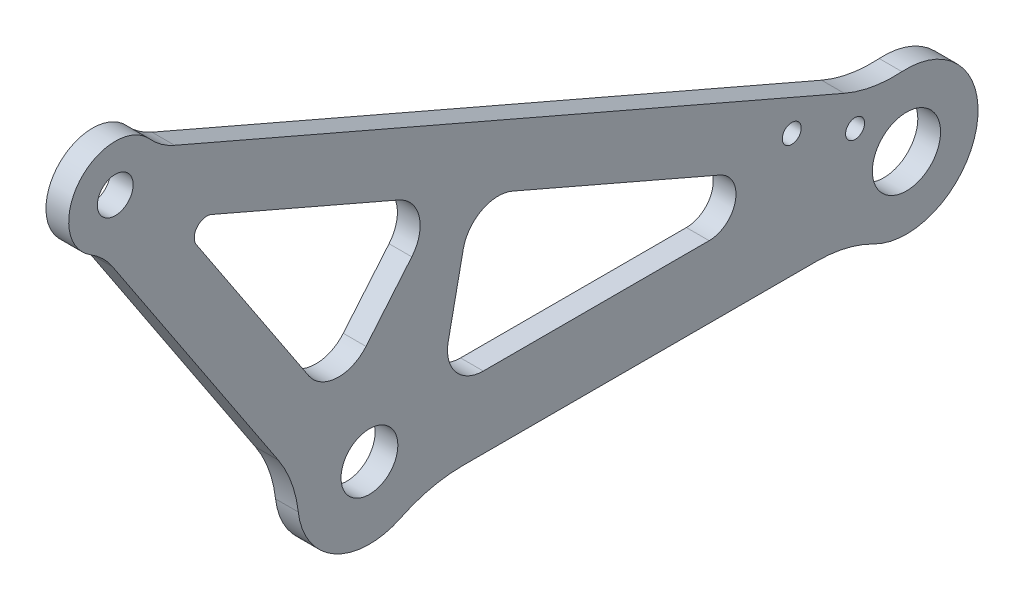
SolidWorks part; units mm, degrees
material "AISI 1020"
ref_plane "Front Plane" through (0, 0, 0) normal (0, 0, 1) x (1, 0, 0)
ref_plane "Top Plane" through (0, 0, 0) normal (0, 1, 0) x (1, 0, 0)
ref_plane "Right Plane" through (0, 0, 0) normal (1, 0, 0) x (0, 0, -1)
sketch "Sketch1" plane through (0, 0, 0) normal (1, 0, 0) x (0, 0, -1)
  line L0 (-60.7171, 0) -> (60.7171, 0)
  line L3 (0, -143.7223) -> (0, 143.7223) construction
  line L4 (-149.7529, 101.5535) -> (-94.5581, 18.1812)
  line L5 (-134.4049, 119.8783) -> (67.4524, 32.5212)
  line L6 (-75, 14) -> (75, 14) construction
  line L8 (-146, 114) -> (-75, 14) construction
  arc A20 (-134.4049, 119.8783) -> (-149.7529, 101.5535) centre (-146, 114) ccw
  arc A22 (-94.5581, 18.1812) -> (-60.7171, 0) centre (-75, 14) ccw
  arc A23 (60.7171, 0) -> (67.4524, 32.5212) centre (75, 14) ccw
  point P5 (0, 0)
  point P14 (0, 0)
  dimension "D3" = 20
  dimension "D5" = 13
  dimension "D6" = 20
  dimension "D4" = 127
  dimension "D7" = 254
  dimension "D10" = 6
  dimension "D11" = 6
  dimension "D9" = 3
  dimension "D12" = 3
  dimension "D13" = 6
  dimension "D14" = 6
  dimension "D2" = 150
  dimension "D8" = 122.6418
extrude "Boss-Extrude1" add sketch "Sketch1" along normal blind 6.35
hole_wizard "3/4 (0.75) Diameter Hole1" positions "Sketch4" profile "Sketch3" hole size "3/4" standard "ANSI Inch" end condition up to next
sketch "Sketch4" plane through (6.35, 0, 0) normal (1, 0, 0) x (0, 0, -1)
  point P5 (75, 14)
sketch "Sketch3" plane through (6.35, 14, -75) normal (0, 1, 0) x (0, 0, -1)
  line L0 (0, 0) -> (0, 6.35)
  line L1 (0, 6.35) -> (9.525, 6.35)
  line L2 (9.525, 6.35) -> (9.525, 0)
  line L5 (9.525, 0) -> (0, 0)
  line L11 (0, -6.35) -> (0, 107.95) construction
  dimension "Thru Hole Dia." = 19.05
  dimension "Thru Hole Depth" = 6.35
hole_wizard "Ø10.0 (10) Diameter Hole1" positions "Sketch9" profile "Sketch6" hole size "Ø10.0" standard "ANSI Metric" end condition up to next
sketch "Sketch9" plane through (6.35, 0, 0) normal (1, 0, 0) x (0, 0, -1)
  point P0 (-146, 114)
sketch "Sketch6" plane through (6.35, 114, 146) normal (0, 1, 0) x (0, 0, -1)
  line L0 (0, 0) -> (0, 6.35)
  line L1 (0, 6.35) -> (5, 6.35)
  line L2 (5, 6.35) -> (5, 0)
  line L5 (5, 0) -> (0, 0)
  line L11 (0, -6.35) -> (0, 107.95) construction
  dimension "Thru Hole Dia." = 10
  dimension "Thru Hole Depth" = 6.35
hole_wizard "Ø5/8\" Diameter Hole2" positions "Sketch16" profile "Sketch11" hole size "5/8" standard "ANSI Inch" end condition up to next
sketch "Sketch16" plane through (6.35, 0, 0) normal (1, 0, 0) x (0, 0, -1)
  line L0 (75, 14) -> (157.5513, 156.983)
  line L2 (0, 0) -> (0, 108.153) construction
  line L4 (-146, 114) -> (-119.4521, 194.8786)
  line L6 (-174.545, 70.324) -> (-178.0536, 59.6351) construction
  line L7 (-174.545, 70.324) -> (-178.0536, 59.6351) construction
  arc A0 (-94.5581, 18.1812) -> (-60.7171, 0) centre (-75, 14) ccw construction
  point P0 (-75, 14)
  dimension "D1" = 30
sketch "Sketch11" plane through (6.35, 14, 75) normal (0, 1, 0) x (0, 0, -1)
  line L0 (0, 0) -> (0, 6.35)
  line L1 (0, 6.35) -> (7.9375, 6.35)
  line L2 (7.9375, 6.35) -> (7.9375, 0)
  line L5 (7.9375, 0) -> (0, 0)
  line L11 (0, -6.35) -> (0, 107.95) construction
  dimension "Thru Hole Dia." = 15.875
  dimension "Thru Hole Depth" = 6.35
sketch "Sketch8" plane through (6.35, 0, 0) normal (1, 0, 0) x (0, 0, -1)
  line L2 (-54.5605, 67.8903) -> (-46.3008, 64.3157) construction
  line L3 (-52.9877, 32.028) -> (-48.7918, 52.2877)
  line L7 (-75.9573, 42.3434) -> (-63.1664, 57.6152)
  line L9 (-123.3455, 90.6494) -> (-91.9619, 43.2441)
  line L10 (-119.037, 95.7935) -> (-66.861, 73.2135)
  line L11 (19.8861, 20) -> (-43.1955, 20)
  line L12 (67.4524, 32.5212) -> (-134.4049, 119.8783) construction
  line L13 (-149.7529, 101.5535) -> (-94.5581, 18.1812) construction
  line L14 (-60.7171, 0) -> (60.7171, 0) construction
  line L15 (-84.5632, 32.0683) -> (-84.2827, 31.6447) construction
  line L16 (-55.4787, 20) -> (-55.9867, 20) construction
  line L17 (-54.5605, 67.8903) -> (-46.3008, 64.3157) construction
  line L18 (-35.0279, 59.4372) -> (22.8649, 34.3831)
  line L19 (-120.4271, 92.5814) -> (-104.3957, 79.1543) construction
  line L20 (19.8861, 27.5) -> (27.9693, 25.826) construction
  line L21 (-29.8567, 10) -> (10.3311, 10) construction
  arc A0 (-52.9877, 32.028) -> (-43.1955, 20) centre (-43.1955, 30) ccw
  arc A2 (-48.7918, 52.2877) -> (-35.0279, 59.4372) centre (-38.9996, 50.2597) cw
  arc A4 (-63.1664, 57.6152) -> (-66.861, 73.2135) centre (-70.8327, 64.0361) ccw
  arc A14 (-119.037, 95.7935) -> (-123.3455, 90.6494) centre (-120.4271, 92.5814) ccw
  arc A20 (-75.9573, 42.3434) -> (-91.9619, 43.2441) centre (-83.6236, 48.7643) cw
  arc A25 (-134.4049, 119.8783) -> (-149.7529, 101.5535) centre (-146, 114) ccw construction
  circle A27 centre (-146, 114) radius 5 construction
  arc A36 (-94.5581, 18.1812) -> (-60.7171, 0) centre (-75, 14) ccw construction
  circle A39 centre (-75, 14) radius 7.9375 construction
  arc A40 (19.8861, 20) -> (22.8649, 34.3831) centre (19.8861, 27.5) ccw
  circle A54 centre (-75, 14) radius 19.9375
  arc A55 (-55.9867, 20) -> (-84.2827, 31.6447) centre (-75, 14) ccw construction
  point P7 (-33.5049, 66.1162)
  point P19 (-33.4763, 76.1997)
  dimension "D8" = 8
  dimension "D9" = 12.0625
  dimension "D11" = 9
  dimension "D7" = 4
  dimension "D1" = 7
  dimension "D10" = 24.8576
  dimension "D2" = 15
  dimension "D12" = 10
  dimension "D13" = 14.6862
  dimension "D3" = 12
  dimension "D5" = 16
  dimension "D6" = 20
  dimension "D4" = 16
extrude "Cut-Extrude1" cut sketch "Sketch8" against normal up to next
fillet "Fillet1" radius 35 1 edges at (3.175, 18.1812, 94.5581)
fillet "Fillet3" radius 35 2 edges at (3.175, 32.5212, -67.4524) (3.175, 0, -60.7171)
fillet "Fillet4" radius 20 2 edges at (3.175, 101.5535, 149.7529) (3.175, 119.8783, 134.4049)
fillet "Fillet6" radius 40 1 edges at (3.175, 0, 60.7171)
sketch "Sketch17" [suppressed] plane through (0, 0, 0) normal (-1, 0, 0) x (0, 0, 1)
  line L0 (-31.692, 47.9971) -> (-74.6306, 61.6169)
  line L1 (-57.6351, 36.7697) -> (129.4114, 117.7173) construction
  line L2 (-134.8033, 70.2122) -> (-137.856, 60.5882)
  line L3 (-135.7084, 50.8215) -> (-89.7688, 0.5136)
  line L4 (-57.6351, 36.7697) -> (-31.692, 47.9971)
  line L6 (-84.0792, 16.8799) -> (-65.9208, 11.1201) construction
  line L7 (-100.5678, 75.614) -> (-71.9719, 66.5436) construction
  line L8 (-77.8799, 4.9208) -> (-72.1201, 23.0792) construction
  line L9 (-74.6306, 61.6169) -> (-101.2349, 70.0556) construction
  line L10 (-101.2349, 70.0556) -> (-122.2479, 76.7207)
  arc A0 (-73.7404, 33.9603) -> (-65.9164, -3.8182) centre (-75, 14) ccw construction
  arc A1 (-73.7404, 33.9603) -> (-57.6351, 36.7697) centre (-71.5361, 68.8908) ccw construction
  arc A2 (-73.7404, 33.9603) -> (-89.7688, 0.5136) centre (-75, 14) ccw
  arc A3 (-73.7404, 33.9603) -> (-57.6351, 36.7697) centre (-71.5361, 68.8908) ccw
  arc A4 (-137.856, 60.5882) -> (-135.7084, 50.8215) centre (-128.324, 57.5647) ccw
  arc A5 (-122.2479, 76.7207) -> (-134.8033, 70.2122) centre (-125.2713, 67.1887) ccw
  arc A6 (-101.2349, 70.0556) -> (-74.6306, 61.6169) centre (-86.2698, 71.0788) ccw
  circle A7 centre (-75, 14) radius 9.525 construction
  arc A8 (-71.9719, 66.5436) -> (-100.5678, 75.614) centre (-86.2698, 71.0788) ccw construction
  arc A9 (-100.5678, 75.614) -> (-101.2349, 70.0556) centre (-86.2698, 71.0788) ccw construction
  arc A10 (-74.6306, 61.6169) -> (-71.9719, 66.5436) centre (-86.2698, 71.0788) ccw construction
  point P15 (-75, 14)
  point P18 (-86.2698, 71.0788)
  point P26 (-139.6016, 55.0849)
  point P29 (-131.7798, 79.7442)
  point P31 (-75, 14)
  dimension "D5" = 10
  dimension "D1" = 41
  dimension "D2" = 45.5
  dimension "D3" = 120
  dimension "D4" = 74
  dimension "D6" = 30
  dimension "D7" = 51
  dimension "D8" = 28
extrude "Boss-Extrude2" [suppressed] add sketch "Sketch17" against normal up to surface (6.35 mm away)
hole_wizard "M5 Clearance Hole1" positions "Sketch21" profile "Sketch19" hole size "M5" standard "ANSI Metric"
sketch "Sketch21" [suppressed] plane through (0, 0, 0) normal (-1, 0, 0) x (0, 0, 1)
  line L0 (-125.2509, 66.6577) -> (-73.9498, 50.3854) construction
  line L2 (-31.692, 47.9971) -> (-74.6306, 61.6169) construction
  line L3 (-75, 14) -> (-64.4178, 47.3619) construction
  line L5 (-134.8033, 70.2122) -> (-137.856, 60.5882) construction
  point P1 (-125.2509, 66.6577)
  point P3 (-73.9498, 50.3854)
  dimension "D1" = 35
  dimension "D2" = 10
  dimension "D3" = 53.82
sketch "Sketch19" plane through (0, 66.6577, -125.2509) normal (0, 1, 0) x (0, 0, 1)
  line L0 (0, 0) -> (0, 6.35)
  line L1 (0, 6.35) -> (2.65, 6.35)
  line L2 (2.65, 6.35) -> (2.65, 0)
  line L5 (2.65, 0) -> (0, 0)
  line L11 (0, -6.35) -> (0, 107.95) construction
  dimension "Thru Hole Dia." = 5.3
  dimension "Thru Hole Depth" = 6.35
fillet "Fillet7" [suppressed] radius 25
fillet "Fillet8" [suppressed] radius 5
sketch "Sketch22" plane through (6.35, 0, 0) normal (1, 0, 0) x (0, 0, -1)
  line L0 (0.2732, 61.5941) -> (-6.0815, 46.9101) construction
  line L1 (57.6351, 36.7697) -> (-129.4114, 117.7173) construction
  line L2 (22.8649, 34.3831) -> (-35.0279, 59.4372) construction
  line L3 (-2.9042, 54.2521) -> (70.5938, 22.4446) construction
  line L4 (70.5938, 22.4446) -> (60.6448, 26.7502) construction
  circle A0 centre (75, 14) radius 9.525 construction
  circle A1 centre (60.6448, 26.7502) radius 2.65
  dimension "D2" = 5.3
  dimension "D1" = 10.8408
extrude "Cut-Extrude2" cut sketch "Sketch22" against normal blind 10
sketch "Sketch24" plane through (6.35, 0, 0) normal (1, 0, 0) x (0, 0, -1)
  line L0 (12.6689, 56.2296) -> (6.3142, 41.5457) construction
  line L1 (57.6351, 36.7697) -> (-129.4114, 117.7173) construction
  line L2 (22.8649, 34.3831) -> (-35.0279, 59.4372) construction
  line L3 (9.4916, 48.8876) -> (70.5938, 22.4446) construction
  line L4 (60.6448, 26.7502) -> (42.9665, 34.4008) construction
  circle A0 centre (75, 14) radius 9.525 construction
  circle A3 centre (42.9665, 34.4008) radius 2.65
  dimension "D1" = 19.2627
  dimension "D2" = 5.3
extrude "Cut-Extrude3" cut sketch "Sketch24" against normal blind 10
equation "\"D11@Sketch1\"=\"D10@Sketch1\""
equation "\"D12@Sketch1\"=\"D9@Sketch1\""
equation "\"D14@Sketch1\"=\"D13@Sketch1\""
